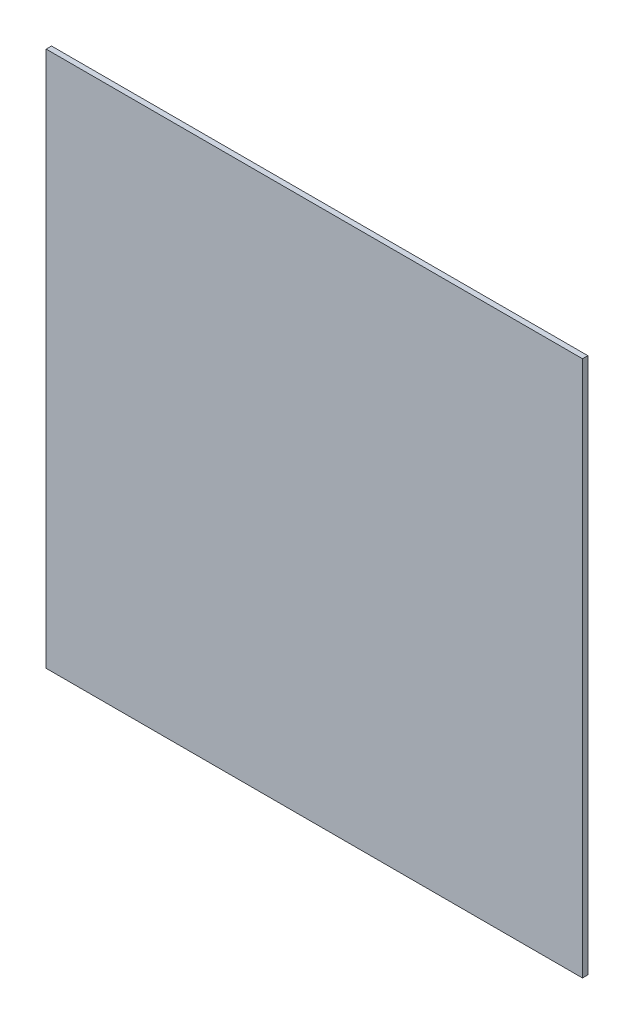
SolidWorks part; units mm, degrees
ref_plane "Plan de face" through (0, 0, 0) normal (0, 0, 1) x (1, 0, 0)
ref_plane "Plan de dessus" through (0, 0, 0) normal (0, 1, 0) x (1, 0, 0)
ref_plane "Plan de droite" through (0, 0, 0) normal (1, 0, 0) x (0, 0, -1)
sketch "Esquisse1" plane through (0, 0, 0) normal (0, 0, 1) x (1, 0, 0)
  line L1 (-100, 100) -> (100, 100)
  line L2 (-100, 100) -> (-100, -100)
  line L3 (-100, -100) -> (100, -100)
  line L4 (100, 100) -> (100, -100)
  line L5 (-100, 100) -> (100, -100) construction
  line L6 (-100, -100) -> (100, 100) construction
  point P0 (0, 0)
  dimension "D1" = 200
  dimension "D2" = 200
extrude "Boss.-Extru.1" add sketch "Esquisse1" along normal blind 2
